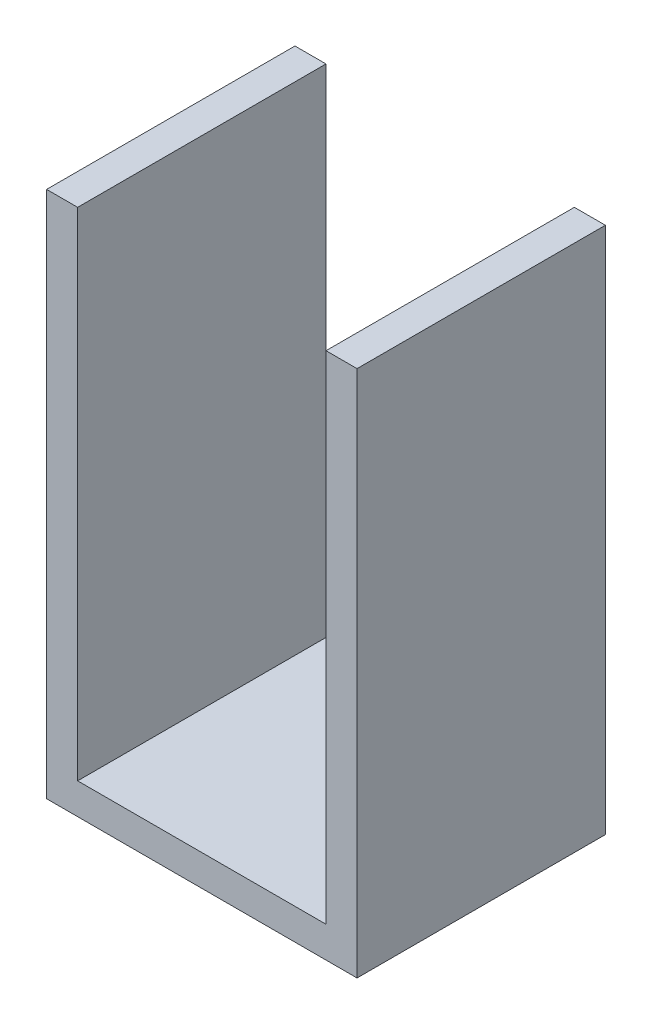
SolidWorks part; units mm, degrees
ref_plane "Front Plane" through (0, 0, 0) normal (0, 0, 1) x (1, 0, 0)
ref_plane "Top Plane" through (0, 0, 0) normal (0, 1, 0) x (1, 0, 0)
ref_plane "Right Plane" through (0, 0, 0) normal (1, 0, 0) x (0, 0, -1)
sketch "Sketch2" plane through (0, 0, 0) normal (0, 1, 0) x (1, 0, 0)
  line L1 (-20, -20) -> (20, -20)
  line L2 (-20, -20) -> (-20, 20)
  line L3 (-20, 20) -> (20, 20)
  line L4 (20, -20) -> (20, 20)
  line L5 (-20, -20) -> (20, 20) construction
  line L6 (-20, 20) -> (20, -20) construction
  point P0 (0, 0)
  dimension "D1" = 40
  dimension "D2" = 40
extrude "Boss-Extrude1" add sketch "Sketch2" along normal blind 5
sketch "Sketch3" plane through (20, 0, 0) normal (1, 0, 0) x (0, 0, -1)
  line L1 (20, 5) -> (-20, 5)
  line L2 (20, 5) -> (20, 0)
  line L3 (20, 0) -> (-20, 0)
  line L4 (-20, 5) -> (-20, 0)
extrude "Boss-Extrude2" add sketch "Sketch3" along normal blind 10
sketch "Sketch4" plane through (0, 5, 0) normal (0, 1, 0) x (1, 0, 0)
  line L0 (-20, -20) -> (30, -20) construction
  line L1 (-20, 20) -> (-15, 20)
  line L2 (-20, 20) -> (-20, -20)
  line L3 (-20, -20) -> (-15, -20)
  line L4 (-15, 20) -> (-15, -20)
  line L6 (30, 20) -> (25, 20)
  line L7 (30, 20) -> (30, -20)
  line L8 (30, -20) -> (25, -20)
  line L9 (25, 20) -> (25, -20)
  dimension "D1" = 5
  dimension "D2" = 5
extrude "Boss-Extrude3" add sketch "Sketch4" along normal blind 80
